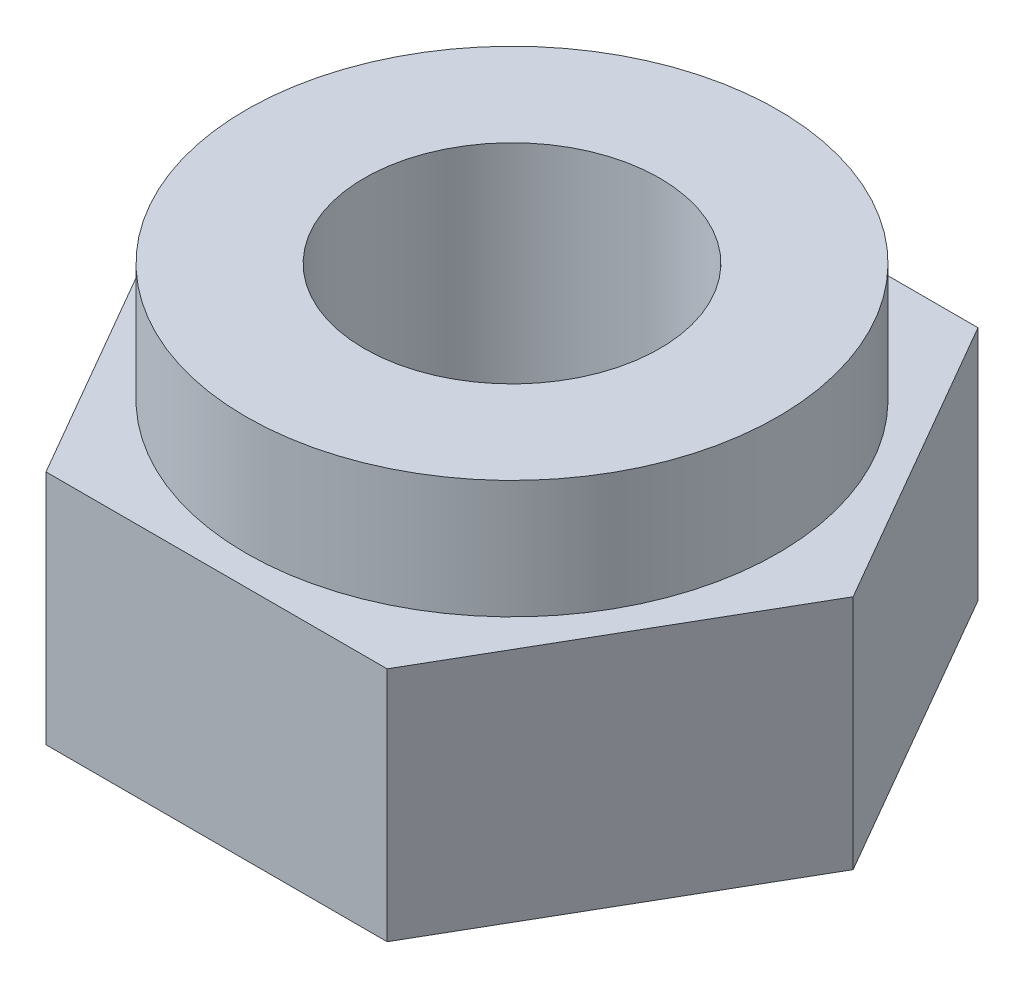
SolidWorks part; units mm, degrees
ref_plane "前视基准面" through (0, 0, 0) normal (0, 0, 1) x (1, 0, 0)
ref_plane "上视基准面" through (0, 0, 0) normal (0, 1, 0) x (1, 0, 0)
ref_plane "右视基准面" through (0, 0, 0) normal (1, 0, 0) x (0, 0, -1)
sketch "草图1" plane through (0, 0, 0) normal (0, 1, 0) x (1, 0, 0)
  line L1 (2.8868, 0) -> (1.4434, 2.5)
  line L2 (1.4434, 2.5) -> (-1.4434, 2.5)
  line L3 (-1.4434, 2.5) -> (-2.8868, 0)
  line L4 (-2.8868, 0) -> (-1.4434, -2.5)
  line L5 (-1.4434, -2.5) -> (1.4434, -2.5)
  line L6 (1.4434, -2.5) -> (2.8868, 0)
  circle A0 centre (0, 0) radius 2.5 construction
  dimension "D1" = 5
extrude "凸台-拉伸1" add sketch "草图1" along normal blind 3
sketch "草图2" plane through (0, 3, 0) normal (0, 1, 0) x (1, 0, 0)
  circle A0 centre (0, 0) radius 1.25
  dimension "D1" = 2.5
extrude "切除-拉伸1" cut sketch "草图2" against normal up to next
cosmetic thread "装饰螺纹线1" parameters "D2"=3.5
sketch "草图3" plane through (0, 3, 0) normal (0, 1, 0) x (1, 0, 0)
  circle A0 centre (0, 0) radius 2.25
  circle A1 centre (0, 0) radius 1.25 construction
  dimension "D1" = 1
extrude "切除-拉伸2" cut sketch "草图3" against normal blind 1 flip side to cut
